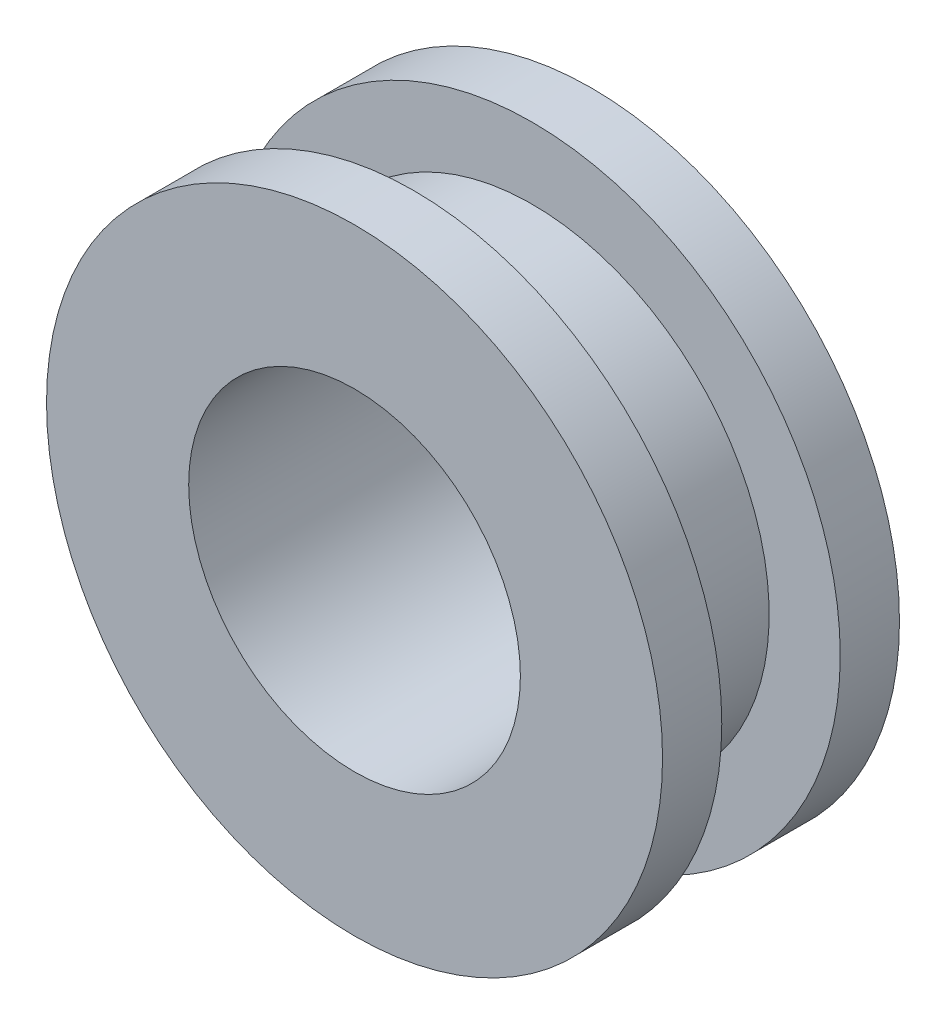
SolidWorks part; units mm, degrees
ref_plane "Plan de face" through (0, 0, 0) normal (0, 0, 1) x (1, 0, 0)
ref_plane "Plan de dessus" through (0, 0, 0) normal (0, 1, 0) x (1, 0, 0)
ref_plane "Plan de droite" through (0, 0, 0) normal (1, 0, 0) x (0, 0, -1)
sketch "Esquisse1" plane through (0, 0, 0) normal (0, 0, 1) x (1, 0, 0)
  circle A0 centre (0, 0) radius 3.5
  circle A1 centre (0, 0) radius 6.5
  dimension "D1" = 7
  dimension "D2" = 13
extrude "Boss.-Extru.1" add sketch "Esquisse1" along normal blind 5
sketch "Esquisse2" plane through (0, 0, 0) normal (0, 1, 0) x (1, 0, 0)
  line L0 (0, 1.6244) -> (0, -6.6244) construction
  line L1 (6.5, -5) -> (6.5, 0) construction
  line L2 (5, -1.25) -> (6.5, -1.25)
  line L3 (5, -1.25) -> (5, -3.75)
  line L4 (5, -3.75) -> (6.5, -3.75)
  line L5 (6.5, -1.25) -> (6.5, -3.75)
  line L6 (5, -1.25) -> (6.5, -3.75) construction
  line L7 (5, -3.75) -> (6.5, -1.25) construction
  line L8 (-7.2879, -2.5) -> (8.0395, -2.5) construction
  line L10 (-6.5, -5) -> (6.5, -5) construction
  point P3 (5.75, -2.5)
  dimension "D1" = 5
  dimension "D2" = 2.5
  dimension "D3" = 2.5
revolve "Enlèvement de matière-Révolution1" cut sketch "Esquisse2" angle 360 about L0
